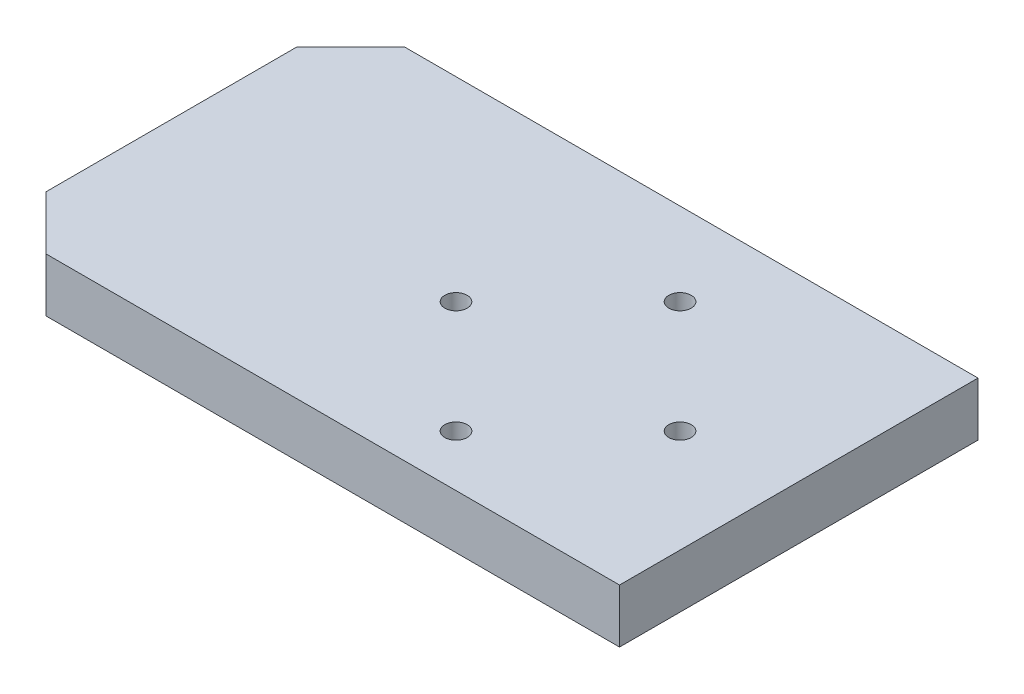
SolidWorks part; units mm, degrees
ref_plane "Front Plane" through (0, 0, 0) normal (0, 0, 1) x (1, 0, 0)
ref_plane "Top Plane" through (0, 0, 0) normal (0, 1, 0) x (1, 0, 0)
ref_plane "Right Plane" through (0, 0, 0) normal (1, 0, 0) x (0, 0, -1)
sketch "Sketch1" plane through (0, 0, 0) normal (0, 1, 0) x (1, 0, 0)
  line L0 (-58, -40) -> (-70, -28)
  line L1 (70, 40) -> (-58, 40)
  line L2 (70, 40) -> (70, -40)
  line L3 (70, -40) -> (-58, -40)
  line L4 (-70, 28) -> (-70, -28)
  line L5 (70, 40) -> (-70, -40) construction
  line L6 (70, -40) -> (-70, 40) construction
  line L7 (210, 0) -> (-70, 0) construction
  line L8 (-58, 40) -> (-70, 28)
  circle A0 centre (22, -3.5) radius 25 construction
  circle A1 centre (22, 21.5) radius 2.5
  circle A2 centre (47, -3.5) radius 2.5
  circle A3 centre (22, -28.5) radius 2.5
  circle A4 centre (-3, -3.5) radius 2.5
  point P0 (0, 0)
  point P11 (70, 0)
  point P18 (0, 0)
  point P19 (0, 0)
  dimension "D3" = 50
  dimension "D8" = 5
  dimension "D1" = 80
  dimension "D2" = 140
  dimension "D4" = 36.5
  dimension "D7" = 48
  dimension "D9" = 4
extrude "Boss-Extrude1" add sketch "Sketch1" along normal blind 12
